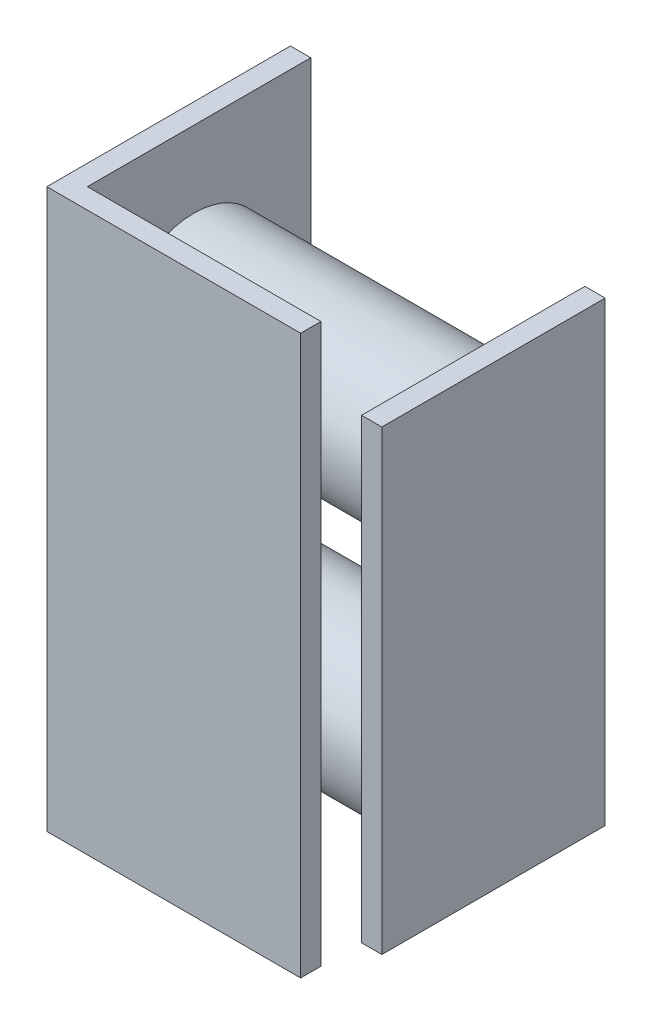
SolidWorks part; units mm, degrees
ref_plane "Front Plane" through (0, 0, 0) normal (0, 0, 1) x (1, 0, 0)
ref_plane "Top Plane" through (0, 0, 0) normal (0, 1, 0) x (1, 0, 0)
ref_plane "Right Plane" through (0, 0, 0) normal (1, 0, 0) x (0, 0, -1)
sketch "Sketch1" plane through (0, 0, 0) normal (0, 1, 0) x (1, 0, 0)
  line L0 (0, 0) -> (25, 0)
  line L1 (25, 0) -> (25, 2)
  line L2 (25, 2) -> (2, 2)
  line L3 (2, 2) -> (2, 24)
  line L4 (2, 24) -> (0, 24)
  line L5 (0, 24) -> (0, 0)
extrude "Boss-Extrude1" add sketch "Sketch1" along normal blind 55
sketch "Sketch2" plane through (0, 0, 0) normal (-1, 0, 0) x (0, 0, 1)
  line L0 (13.2, 0) -> (-13.2, 0) construction
  line L2 (-24, 55) -> (0, 55) construction
  line L3 (0, 55) -> (0, 0) construction
  circle A0 centre (-12.5, 15) radius 7.5
  circle A1 centre (-12.5, 40) radius 7.5
  dimension "D1" = 15
  dimension "D2" = 15
  dimension "D3" = 15
  dimension "D4" = 15
  dimension "D5" = 12.5
  dimension "D6" = 12.5
extrude "Boss-Extrude2" add sketch "Sketch2" along normal blind 1 and the other way blind 30
ref_plane "Plane1" through (30, 0, 0) normal (1, 0, 0) x (0, 0, -1)
sketch "Sketch4" plane through (30, 0, 0) normal (1, 0, 0) x (0, 0, -1)
  line L0 (24, 55) -> (24, 0) construction
  line L1 (1, 50) -> (23, 50)
  line L2 (1, 50) -> (1, 5)
  line L3 (1, 5) -> (23, 5)
  line L4 (23, 50) -> (23, 5)
  line L5 (1, 50) -> (23, 5) construction
  line L6 (1, 5) -> (23, 50) construction
  line L9 (24, 48.8015) -> (23, 48.8015) construction
  line L10 (1, 46.8804) -> (0, 46.8804) construction
  line L11 (0, 55) -> (0, 0) construction
  line L12 (16.3937, 50) -> (16.3937, 55) construction
  line L13 (2, 55) -> (24, 55) construction
  line L14 (16.3937, 5) -> (16.3937, 0) construction
  line L15 (13.2, 0) -> (-13.2, 0) construction
  point P0 (12, 27.5)
  dimension "D1" = 45
  dimension "D2" = 22
extrude "Boss-Extrude3" add sketch "Sketch4" along normal blind 2 separate body
